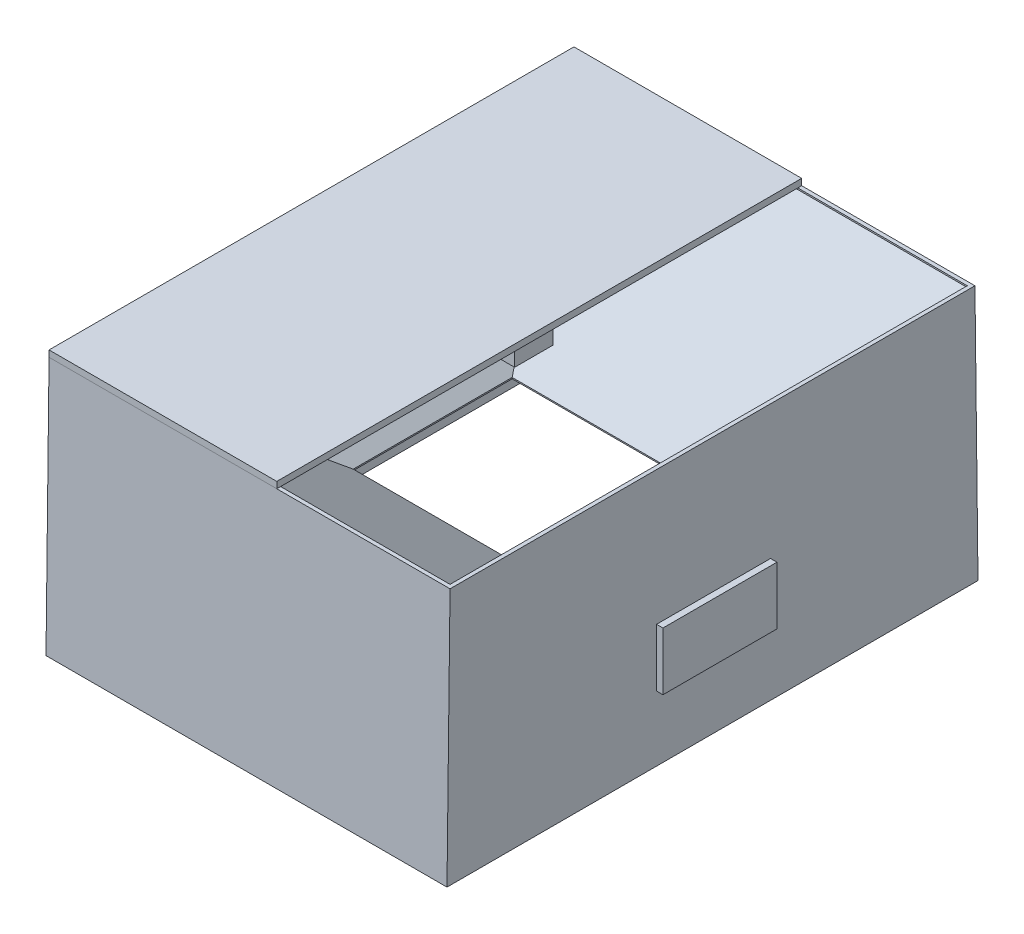
SolidWorks part; units mm, degrees
ref_plane "Alzado" through (0, 0, 0) normal (0, 0, 1) x (1, 0, 0)
ref_plane "Planta" through (0, 0, 0) normal (0, 1, 0) x (1, 0, 0)
ref_plane "Vista lateral" through (0, 0, 0) normal (1, 0, 0) x (0, 0, -1)
sketch "Croquis1" plane through (0, 0, 0) normal (0, 1, 0) x (1, 0, 0)
  line L1 (-125, 125) -> (125, 125)
  line L2 (-125, 125) -> (-125, -125)
  line L3 (-125, -125) -> (125, -125)
  line L4 (125, 125) -> (125, -125)
  line L5 (-125, 125) -> (125, -125) construction
  line L6 (-125, -125) -> (125, 125) construction
  point P0 (0, 0)
  dimension "D1" = 250
  dimension "D2" = 250
ref_plane "Plano1" through (0, 200, 0) normal (0, 1, 0) x (1, 0, 0)
sketch "Croquis2" plane through (0, 200, 0) normal (0, 1, 0) x (1, 0, 0)
  line L1 (-311.8, 408.8) -> (311.8, 408.8)
  line L2 (-311.8, 408.8) -> (-311.8, -408.8)
  line L3 (-311.8, -408.8) -> (311.8, -408.8)
  line L4 (311.8, 408.8) -> (311.8, -408.8)
  line L5 (-311.8, 408.8) -> (311.8, -408.8) construction
  line L6 (-311.8, -408.8) -> (311.8, 408.8) construction
  point P0 (0, 0)
  dimension "D1" = 623.6
  dimension "D2" = 817.6
loft "Recubrir1" add profiles "Croquis2", "Croquis1"
shell "Vaciado1" thickness 2
sketch "Croquis3" plane through (0, 2, 0) normal (0, 1, 0) x (1, 0, 0)
  line L1 (-124.1313, 124.3661) -> (124.1313, 124.3661)
  line L2 (-124.1313, 124.3661) -> (-124.1313, -124.3661)
  line L3 (-124.1313, -124.3661) -> (124.1313, -124.3661)
  line L4 (124.1313, 124.3661) -> (124.1313, -124.3661)
  line L5 (-124.1313, 124.3661) -> (124.1313, -124.3661) construction
  line L6 (-124.1313, -124.3661) -> (124.1313, 124.3661) construction
  point P0 (0, 0)
extrude "Cortar-Extruir1" cut sketch "Croquis3" against normal blind 10
ref_plane "Plano2" through (0, -200, 0) normal (0, 1, 0) x (1, 0, 0)
sketch "Croquis4" plane through (0, -200, 0) normal (0, 1, 0) x (1, 0, 0)
  line L1 (-311.8, 413.55) -> (311.8, 413.55)
  line L2 (-311.8, 413.55) -> (-311.8, -413.55)
  line L3 (-311.8, -413.55) -> (311.8, -413.55)
  line L4 (311.8, 413.55) -> (311.8, -413.55)
  line L5 (-311.8, 413.55) -> (311.8, -413.55) construction
  line L6 (-311.8, -413.55) -> (311.8, 413.55) construction
  point P0 (0, 0)
  dimension "D1" = 827.1
  dimension "D2" = 623.6
sketch "Croquis5" plane through (0, 200, 0) normal (0, 1, 0) x (1, 0, 0)
  line L1 (-311.8, 408.8) -> (311.8, 408.8)
  line L2 (-311.8, 408.8) -> (-311.8, -408.8)
  line L3 (-311.8, -408.8) -> (311.8, -408.8)
  line L4 (311.8, 408.8) -> (311.8, -408.8)
  line L5 (-311.8, 408.8) -> (311.8, -408.8) construction
  line L6 (-311.8, -408.8) -> (311.8, 408.8) construction
  point P0 (0, 0)
loft "Recubrir3" add profiles "Croquis4", "Croquis5"
shell "Vaciado2" thickness 2
shell "Vaciado5" thickness 2
sketch "Croquis6" plane through (0, -198, 0) normal (0, -1, 0) x (1, 0, 0)
  line L1 (-311.8, 413.55) -> (311.8, 413.55)
  line L2 (-311.8, 413.55) -> (-311.8, -413.55)
  line L3 (-311.8, -413.55) -> (311.8, -413.55)
  line L4 (311.8, 413.55) -> (311.8, -413.55)
  line L5 (-311.8, 413.55) -> (311.8, -413.55) construction
  line L6 (-311.8, -413.55) -> (311.8, 413.55) construction
  point P0 (0, 0)
extrude "Cortar-Extruir2" cut sketch "Croquis6" against normal blind 2
sketch "Croquis9" plane through (313.8, 0, 0) normal (1, 0, 0) x (0, 0, -1)
  line L1 (-87.5376, -7.7378) -> (90.8296, -7.7378)
  line L2 (-87.5376, -7.7378) -> (-87.5376, -98.2094)
  line L3 (-87.5376, -98.2094) -> (90.8296, -98.2094)
  line L4 (90.8296, -7.7378) -> (90.8296, -98.2094)
  line L5 (-87.5376, -7.7378) -> (90.8296, -98.2094) construction
  line L6 (-87.5376, -98.2094) -> (90.8296, -7.7378) construction
  point P0 (1.646, -52.9736)
  point P5 (46.2378, -98.2094)
  dimension "D1" = 200
extrude "Saliente-Extruir3" add sketch "Croquis9" along normal blind 10
sketch "Croquis8" plane through (0, 202, 0) normal (0, 1, 0) x (1, 0, 0)
  line L1 (-313.8, 410.7764) -> (42.6136, 410.7764)
  line L2 (-313.8, 410.7764) -> (-313.8, -410.7764)
  line L3 (-313.8, -410.7764) -> (42.6136, -410.7764)
  line L4 (42.6136, 410.7764) -> (42.6136, -410.7764)
  line L5 (-313.8, -410.7764) -> (313.8, -410.7764) construction
  point P5 (-3.638, -410.7764)
extrude "Saliente-Extruir2" add sketch "Croquis8" along normal blind 10
sketch "Croquis10" plane through (0, 202, 0) normal (0, -1, 0) x (1, 0, 0)
  line L1 (12.8663, 30.023) -> (34.1256, 30.023)
  line L2 (12.8663, 30.023) -> (12.8663, -30.023)
  line L3 (12.8663, -30.023) -> (34.1256, -30.023)
  line L4 (34.1256, 30.023) -> (34.1256, -30.023)
  line L5 (12.8663, 30.023) -> (34.1256, -30.023) construction
  line L6 (12.8663, -30.023) -> (34.1256, 30.023) construction
  point P0 (23.496, 0)
extrude "Saliente-Extruir4" add sketch "Croquis10" along normal blind 30
